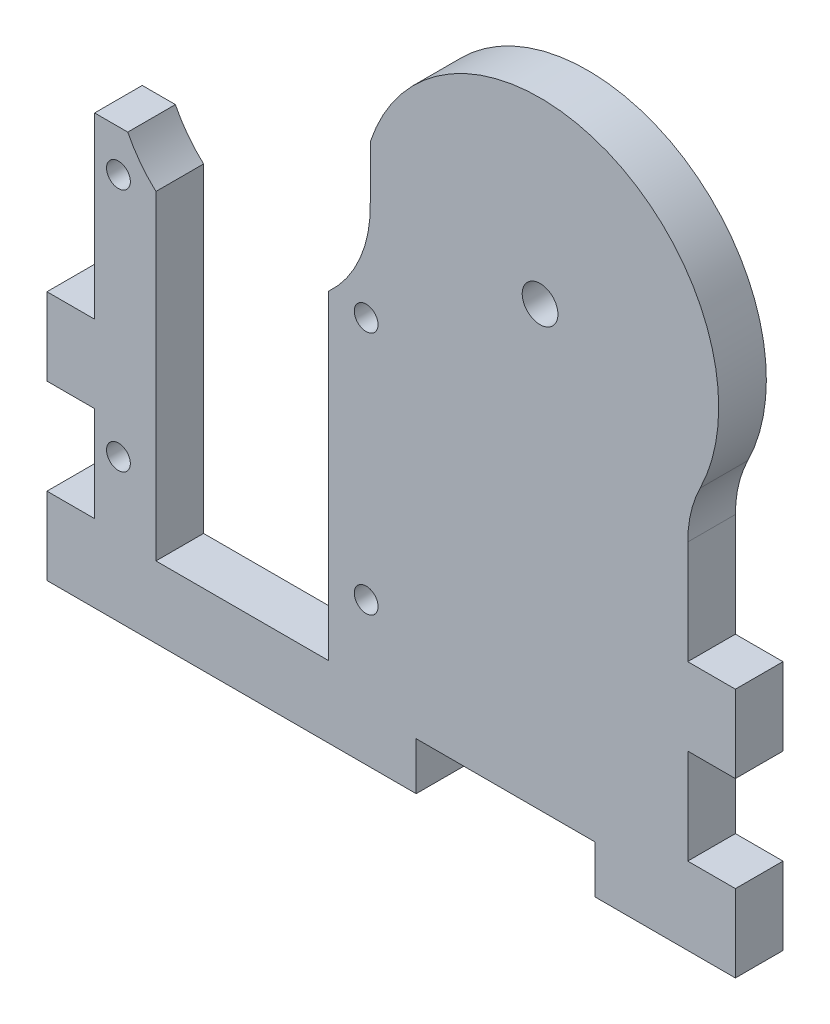
SolidWorks part; units mm, degrees
ref_plane "Спереди" through (0, 0, 0) normal (0, 0, 1) x (1, 0, 0)
ref_plane "Сверху" through (0, 0, 0) normal (0, 1, 0) x (1, 0, 0)
ref_plane "Справа" through (0, 0, 0) normal (1, 0, 0) x (0, 0, -1)
other "Configuration Table"
sketch "Эскиз1" plane through (0, 0, 0) normal (0, 0, 1) x (1, 0, 0)
  line L0 (12.4, 0) -> (12.4, 21.8319) construction
  line L2 (0, 0) -> (0, 30)
  line L5 (0, 16.25) -> (16.6505, 16.25) construction
  line L6 (5.15, 0) -> (5.15, 26.8668)
  line L7 (19.65, 0) -> (19.65, 26.8668)
  line L10 (0, 0) -> (0, -6)
  line L11 (0, -6) -> (49.8, -6)
  line L12 (49.8, -6) -> (49.8, 23.7027)
  line L14 (5.15, 0) -> (19.65, 0)
  line L15 (2.7831, 30) -> (0, 30)
  line L16 (23.1455, 35.1157) -> (23.1455, 39.474)
  line L17 (37.4, 34.804) -> (12.4, 34.804) construction
  line L18 (24.9, 34.804) -> (24.9, -6) construction
  circle A0 centre (2, 26.5) radius 1
  circle A1 centre (22.8, 26.5) radius 1
  circle A2 centre (22.8, 6) radius 1
  circle A3 centre (2, 6) radius 1
  arc A4 (2.7831, 30) -> (5.15, 26.8668) centre (12.4, 34.804) ccw
  arc A5 (19.65, 26.8668) -> (23.1455, 35.1157) centre (12.4, 34.804) ccw
  circle A6 centre (37.4, 34.804) radius 1.5
  arc A7 (50.84, 28.1432) -> (23.1455, 39.474) centre (37.4, 34.804) ccw
  arc A8 (49.8, 23.7027) -> (50.84, 28.1432) centre (59.8, 23.7027) cw
  dimension "D3" = 2
  dimension "D9" = 21.5
  dimension "D6" = 3
  dimension "D13" = 30
  dimension "D14" = 10
  dimension "D2" = 25
  dimension "D4" = 20.5
  dimension "D5" = 20.8
  dimension "D7" = 2
  dimension "D8" = 6
  dimension "D10" = 14.5
  dimension "D11" = 36
  dimension "D12" = 6
extrude "Бобышка-Вытянуть1" add sketch "Эскиз1" along normal blind 4
sketch "Эскиз2" plane through (0, 0, 4) normal (0, 0, 1) x (1, 0, 0)
  line L0 (37.4, 34.804) -> (12.4, 34.804) construction
  line L1 (24.9, 34.804) -> (24.9, -6) construction
  line L2 (0, -6) -> (49.8, -6) construction
  line L4 (27, -6) -> (42, -6)
  line L5 (27, -6) -> (27, -2)
  line L6 (27, -2) -> (42, -2)
  line L7 (42, -6) -> (42, -2)
  dimension "D1" = 27
  dimension "D2" = 15
  dimension "D3" = 4
extrude "Вырез-Вытянуть1" cut sketch "Эскиз2" against normal blind 10
sketch "Эскиз3" plane through (0, 0, 4) normal (0, 0, 1) x (1, 0, 0)
  line L0 (49.8, -6) -> (49.8, 23.7027) construction
  line L1 (0, -6) -> (-4, -6)
  line L2 (0, -6) -> (0, 0.5)
  line L3 (0, 15) -> (-4, 15)
  line L4 (-4, -6) -> (-4, 0.5)
  line L5 (49.8, 15) -> (53.8, 15)
  line L6 (49.8, 15) -> (49.8, 8.5)
  line L7 (49.8, -6) -> (53.8, -6)
  line L8 (53.8, 15) -> (53.8, 8.5)
  line L9 (-4, 8.5) -> (0, 8.5)
  line L10 (-4, 4.5) -> (53.5, 4.5) construction
  line L11 (-4, 0.5) -> (0, 0.5)
  line L12 (-4, 8.5) -> (-4, 15)
  line L13 (0, 8.5) -> (0, 15)
  line L14 (49.8, 8.5) -> (53.8, 8.5)
  line L15 (49.8, 0.5) -> (53.8, 0.5)
  line L16 (49.8, 0.5) -> (49.8, -6)
  line L17 (53.8, 0.5) -> (53.8, -6)
  dimension "D1" = 21
  dimension "D2" = 4
  dimension "D3" = 21
  dimension "D4" = 4
  dimension "D5" = 8
extrude "Бобышка-Вытянуть2" add sketch "Эскиз3" against normal blind 4
